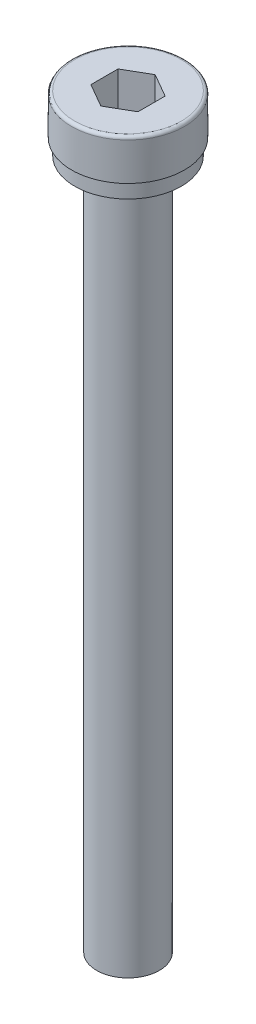
SolidWorks part; units mm, degrees
ref_plane "Front Plane" through (0, 0, 0) normal (0, 0, 1) x (1, 0, 0)
ref_plane "Top Plane" through (0, 0, 0) normal (0, 1, 0) x (1, 0, 0)
ref_plane "Right Plane" through (0, 0, 0) normal (1, 0, 0) x (0, 0, -1)
sketch "Sketch1" plane through (0, 0, 0) normal (1, 0, 0) x (0, 0, -1)
  line L0 (0, 0) -> (0, -23.8)
  line L1 (0, -23.8) -> (1, -23.8)
  line L2 (1, -23.8) -> (1, -1.8)
  line L3 (1, -1.8) -> (1.8, -1.8)
  line L4 (1.8, -1.8) -> (1.8, 0)
  line L5 (1.8, 0) -> (0, 0)
  line L6 (0, 0) -> (0, 14.8278) construction
  dimension "D1" = 22
  dimension "D2" = 1.8
  dimension "D3" = 2
  dimension "D4" = 3.6
revolve "Revolve1" add sketch "Sketch1" angle 360 about L6
sketch "Sketch2" plane through (0, 0, 0) normal (0, 1, 0) x (1, 0, 0)
  line L1 (0, 0.866) -> (-0.75, 0.433)
  line L2 (-0.75, 0.433) -> (-0.75, -0.433)
  line L3 (-0.75, -0.433) -> (0, -0.866)
  line L4 (0, -0.866) -> (0.75, -0.433)
  line L5 (0.75, -0.433) -> (0.75, 0.433)
  line L6 (0.75, 0.433) -> (0, 0.866)
  circle A0 centre (0, 0) radius 0.75 construction
  dimension "D1" = 1.5
extrude "Cut-Extrude1" cut sketch "Sketch2" against normal blind 1.3
fillet "Fillet1" radius 0.1 1 edges at (0, 0, -1.8)
sketch "Sketch3" plane through (0, -1.8, 0) normal (0, -1, 0) x (1, 0, 0)
  circle A0 centre (0, 0) radius 1.8 construction
  circle A1 centre (0, 0) radius 1.8
  circle A2 centre (0, 0) radius 1.7
  dimension "D1" = 0.1
extrude "Cut-Extrude2" cut sketch "Sketch3" against normal blind 0.5
